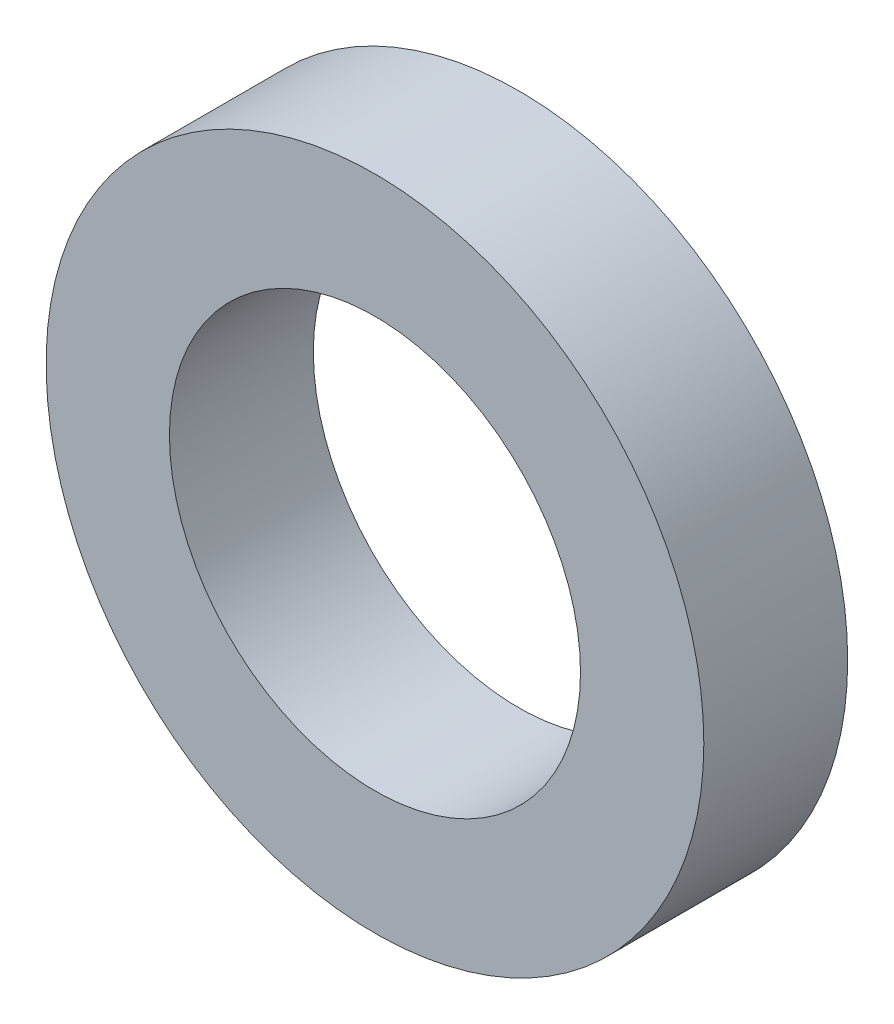
SolidWorks part; units mm, degrees
material "Пластичное железо (SN)"
ref_plane "Спереди" through (0, 0, 0) normal (0, 0, 1) x (1, 0, 0)
ref_plane "Сверху" through (0, 0, 0) normal (0, 1, 0) x (1, 0, 0)
ref_plane "Справа" through (0, 0, 0) normal (1, 0, 0) x (0, 0, -1)
sketch "Эскиз1" plane through (0, 0, 0) normal (0, 0, 1) x (1, 0, 0)
  circle A0 centre (0, 0) radius 10
  circle A1 centre (0, 0) radius 16
  dimension "D1" = 20
  dimension "D2" = 32
extrude "Вытянуть1" add sketch "Эскиз1" along normal blind 7
